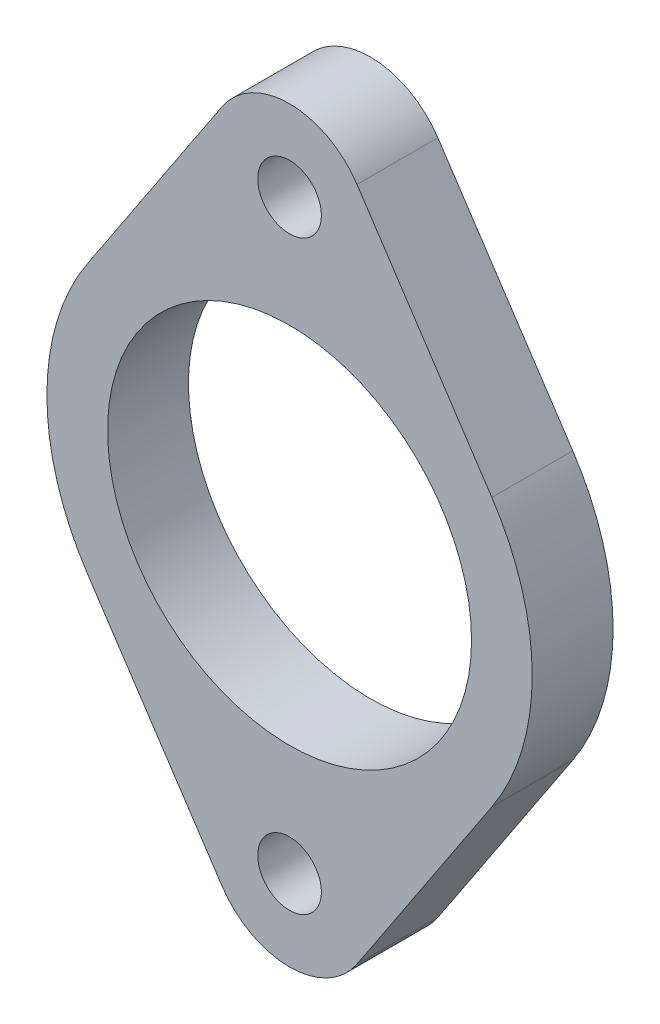
SolidWorks part; units mm, degrees
material "6061-T6 (SS)"
ref_plane "Front Plane" through (0, 0, 0) normal (0, 0, 1) x (1, 0, 0)
ref_plane "Top Plane" through (0, 0, 0) normal (0, 1, 0) x (1, 0, 0)
ref_plane "Right Plane" through (0, 0, 0) normal (1, 0, 0) x (0, 0, -1)
sketch "Sketch1" plane through (0, 0, 0) normal (0, 0, 1) x (1, 0, 0)
  line L0 (0, 0) -> (0, 40) construction
  line L1 (-5.2942, 26.5063) -> (-15.8825, 10.5189)
  line L2 (5.2942, 26.5063) -> (15.8825, 10.5189)
  line L3 (0, 0) -> (14.2875, 0) construction
  line L4 (5.2942, -26.5063) -> (15.8825, -10.5189)
  line L5 (-5.2942, -26.5063) -> (-15.8825, -10.5189)
  circle A0 centre (0, 0) radius 14.2875
  arc A1 (-15.8825, 10.5189) -> (-15.8825, -10.5189) centre (0, 0) ccw
  arc A2 (5.2942, 26.5063) -> (-5.2942, 26.5063) centre (0, 23) ccw
  arc A3 (5.2942, -26.5063) -> (-5.2942, -26.5063) centre (0, -23) cw
  arc A4 (15.8825, -10.5189) -> (15.8825, 10.5189) centre (0, 0) ccw
  point P4 (0, 23)
  dimension "D1" = 28.575
  dimension "D2" = 38.1
  dimension "D5" = 12.7
  dimension "D3" = 40
  dimension "D4" = 17
extrude "Boss-Extrude1" add sketch "Sketch1" along normal mid plane 6.35
hole_wizard "Ø5.0mm Dowel Hole1" positions "Sketch2" profile "Sketch3" hole size "Ø5.0" standard "ANSI Metric" end condition through all
sketch "Sketch2" plane through (0, 0, 3.175) normal (0, 0, 1) x (1, 0, 0)
  point P0 (0, 23)
  point P3 (0, -23)
sketch "Sketch3" plane through (0, 23, 3.175) normal (1, 0, 0) x (0, -1, 0)
  line L0 (0, 0) -> (0, 6.35)
  line L1 (0, 6.35) -> (2.5, 6.35)
  line L2 (2.5, 6.35) -> (2.5, 0)
  line L5 (2.5, 0) -> (0, 0)
  line L11 (0, -6.35) -> (0, 107.95) construction
  dimension "Thru Hole Dia." = 5
  dimension "Thru Hole Depth" = 6.35
equation "\"D1@Sketch1\"=1.125in"
equation "\"D2@Sketch1\"=1.5in"
equation "\"D5@Sketch1\"=0.5in"
